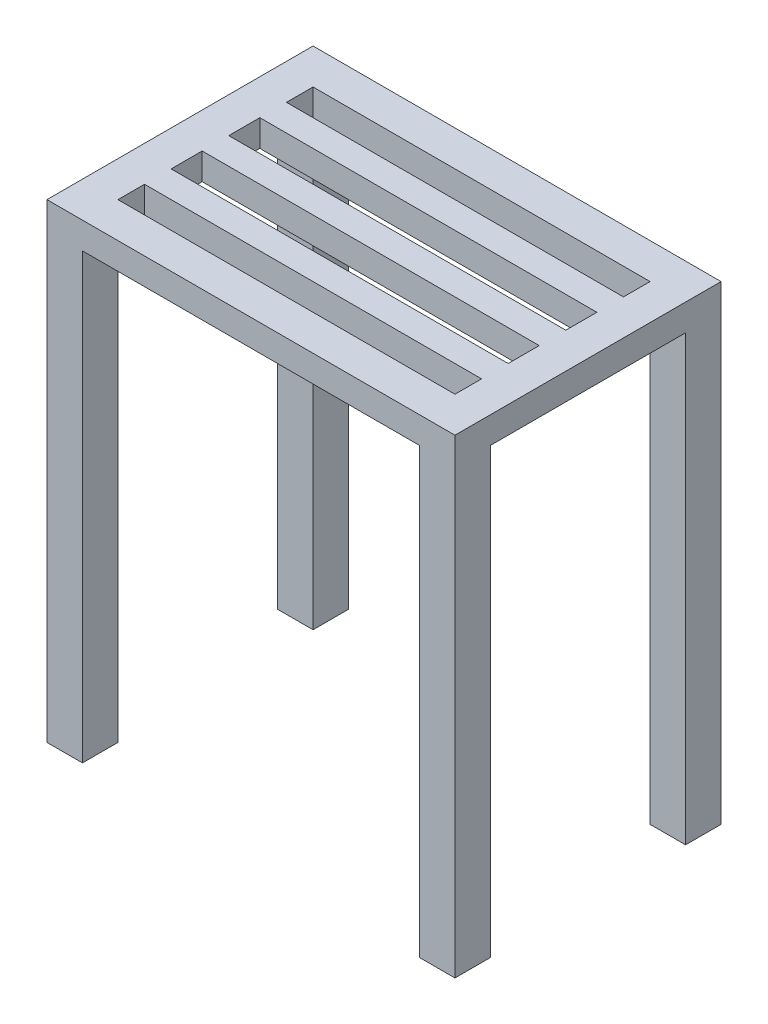
SolidWorks part; units mm, degrees
material "Cast Stainless Steel"
ref_plane "Front Plane" through (0, 0, 0) normal (0, 0, 1) x (1, 0, 0)
ref_plane "Top Plane" through (0, 0, 0) normal (0, 1, 0) x (1, 0, 0)
ref_plane "Right Plane" through (0, 0, 0) normal (1, 0, 0) x (0, 0, -1)
sketch "Sketch1" plane through (0, 0, 0) normal (0, 1, 0) x (1, 0, 0)
  line L0 (0, 0) -> (-230, 0) construction
  line L1 (-230, 150) -> (-190, 150)
  line L2 (-230, 150) -> (-230, 110)
  line L3 (-230, 110) -> (-190, 110)
  line L4 (-190, 150) -> (-190, 110)
  line L5 (-230, 150) -> (-190, 110) construction
  line L6 (-230, 110) -> (-190, 150) construction
  line L7 (0, 0) -> (0, 150) construction
  line L8 (-230, -150) -> (-190, -110) construction
  line L9 (-230, -110) -> (-190, -150) construction
  line L10 (-230, -110) -> (-190, -110)
  line L11 (-230, -150) -> (-230, -110)
  line L12 (-230, -150) -> (-190, -150)
  line L13 (-190, -150) -> (-190, -110)
  line L14 (230, -150) -> (190, -150)
  line L15 (190, -150) -> (190, -110)
  line L16 (230, -150) -> (190, -110) construction
  line L17 (230, -110) -> (190, -150) construction
  line L18 (230, -150) -> (230, -110)
  line L19 (230, -110) -> (190, -110)
  line L20 (190, 150) -> (190, 110)
  line L21 (230, 110) -> (190, 110)
  line L22 (230, 110) -> (190, 150) construction
  line L23 (230, 150) -> (190, 110) construction
  line L24 (230, 150) -> (230, 110)
  line L25 (230, 150) -> (190, 150)
  point P0 (-210, 130)
  dimension "D1" = 40
  dimension "D2" = 230
  dimension "D3" = 150
extrude "Boss-Extrude1" add sketch "Sketch1" along normal blind 500
sketch "Sketch2" plane through (0, 500, 0) normal (0, 1, 0) x (1, 0, 0)
  line L0 (-230, 150) -> (230, 150)
  line L1 (230, 150) -> (230, -150)
  line L2 (230, -150) -> (-230, -150)
  line L3 (-230, -150) -> (-230, 150)
  line L4 (-190, 110) -> (190, 110)
  line L5 (190, 110) -> (190, -110)
  line L6 (190, -110) -> (-190, -110)
  line L7 (-190, -110) -> (-190, 110)
extrude "Boss-Extrude2" add sketch "Sketch2" along normal blind 30
sketch "Sketch4" plane through (-190, 0, 0) normal (1, 0, 0) x (0, 0, -1)
  line L0 (-150, 530) -> (150, 530) construction
  line L1 (-80, 530) -> (-50, 530)
  line L2 (-80, 530) -> (-80, 500)
  line L3 (-80, 500) -> (-50, 500)
  line L4 (-50, 530) -> (-50, 500)
  line L5 (-110, 500) -> (110, 500) construction
  line L6 (-110, 500) -> (-110, 0) construction
  line L7 (-15, 530) -> (15, 530)
  line L8 (-15, 530) -> (-15, 500)
  line L9 (-15, 500) -> (15, 500)
  line L10 (15, 530) -> (15, 500)
  line L11 (50, 530) -> (80, 530)
  line L12 (50, 530) -> (50, 500)
  line L13 (50, 500) -> (80, 500)
  line L14 (80, 530) -> (80, 500)
  line L15 (110, 500) -> (110, 0) construction
  dimension "D1" = 30
  dimension "D2" = 30
  dimension "D3" = 30
  dimension "D4" = 30
  dimension "D5" = 30
  dimension "D6" = 35
extrude "Boss-Extrude4" add sketch "Sketch4" along normal up to next
